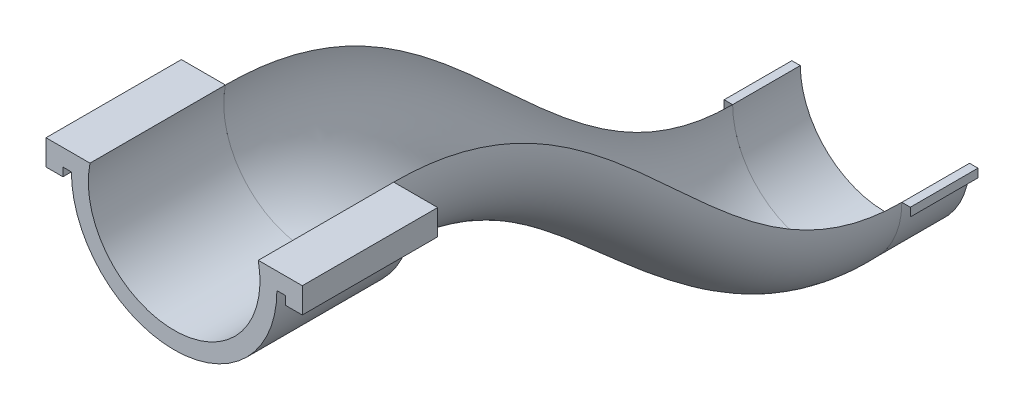
SolidWorks part; units mm, degrees
ref_plane "Front Plane" through (0, 0, 0) normal (0, 0, 1) x (1, 0, 0)
ref_plane "Top Plane" through (0, 0, 0) normal (0, 1, 0) x (1, 0, 0)
ref_plane "Right Plane" through (0, 0, 0) normal (1, 0, 0) x (0, 0, -1)
sketch "Sketch1" plane through (0, 0, 0) normal (0, 0, 1) x (1, 0, 0)
  line L0 (60.7192, 200) -> (65.722, 200)
  line L1 (65.722, 200) -> (65.722, 195)
  line L2 (-60.7192, 200) -> (-65.7192, 200)
  line L3 (-65.7192, 200) -> (-65.7192, 195)
  arc A0 (60.7192, 200) -> (-60.7192, 200) centre (0, 200) cw
  dimension "D1" = 200
ref_plane "Plane1" through (0, 0, -300) normal (0, 0, 1) x (1, 0, 0)
sketch "Sketch2" plane through (0, 0, -300) normal (0, 0, 1) x (1, 0, 0)
  line L0 (49.9996, 49.799) -> (54.9996, 49.799)
  line L1 (54.9996, 49.799) -> (54.9996, 44.799)
  line L2 (-49.9996, 49.799) -> (-54.9996, 49.799)
  line L3 (-54.9996, 49.799) -> (-54.9996, 44.799)
  arc A0 (49.9996, 49.799) -> (-49.9996, 49.799) centre (0, 50) cw
surface "Surface-Extrude1" sketch "Sketch2" parameters "D1"=40
extrude "Extrude-Thin1" add sketch "Sketch1" along normal blind 80 thin contours L1 L0 A0 L2 L3 thin type one direction wall 10
sketch3d "3DSketch1"
  line L0 (49.9996, 49.799, -300) -> (49.9996, 49.799, -340) construction
  line L1 (-49.9996, 49.799, -300) -> (-49.9996, 49.799, -340) construction
  line L2 (-49.7237, 210, 80) -> (-49.7237, 210, 0) construction
  line L3 (49.9996, 49.799, -300) -> (49.9996, 49.799, -340)
  line L4 (-49.9996, 49.799, -300) -> (-49.9996, 49.799, -340)
  line L5 (-49.7237, 210, 80) -> (-49.7237, 210, 0)
  line L6 (49.7237, 210, 80) -> (49.7237, 210, 0) construction
  spline S0 degree 3 poles (-49.9996, 49.799, -300) (-49.9996, 49.799, -186.6351) (-49.7237, 210, -137.5211) (-49.7237, 210, 0) knots 0 0 0 0 1 1 1 1
  spline S1 degree 3 poles (49.9996, 49.799, -300) (49.9996, 49.799, -186.6351) (49.7237, 210, -137.5211) (49.7237, 210, 0) knots 0 0 0 0 1 1 1 1
  point P7 (0, 0, 0)
surface "Surface-Loft2"
